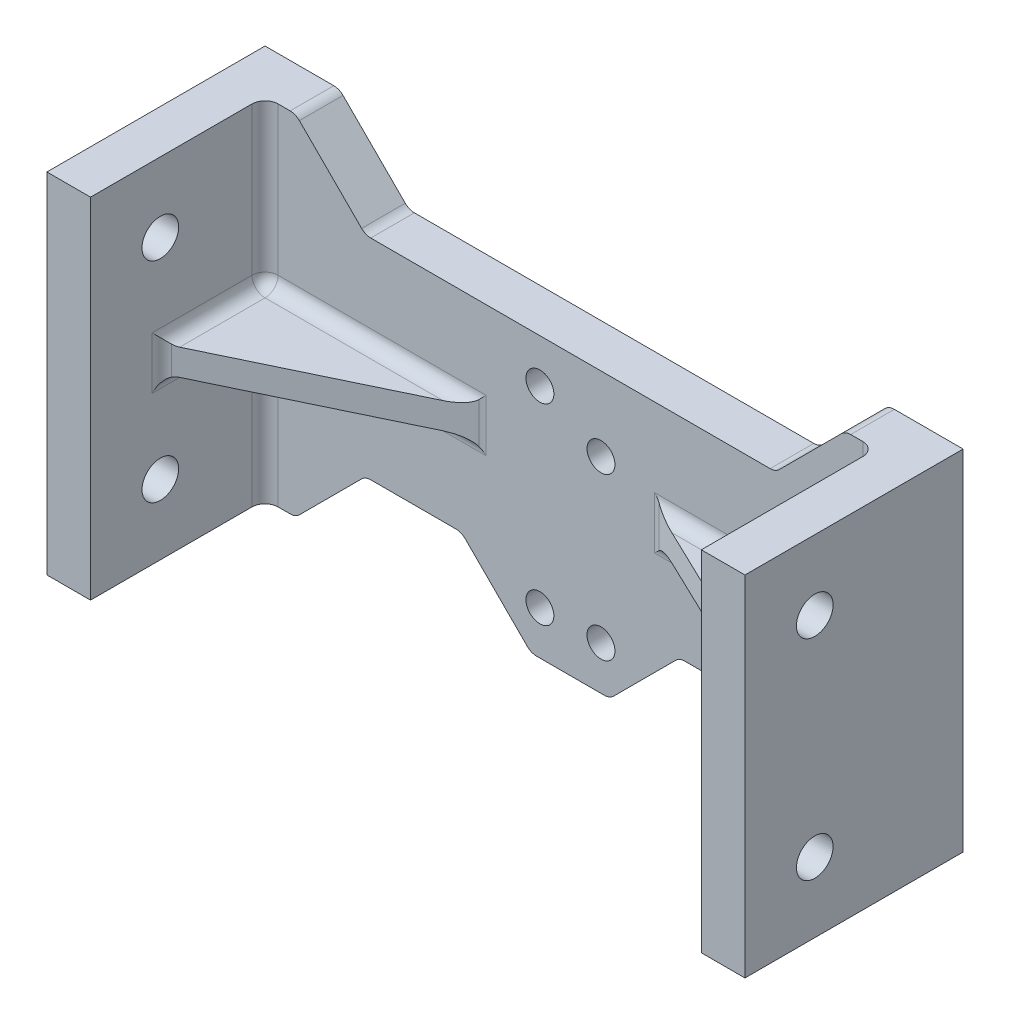
SolidWorks part; units mm, degrees
ref_plane "前视基准面" through (0, 0, 0) normal (0, 0, 1) x (1, 0, 0)
ref_plane "上视基准面" through (0, 0, 0) normal (0, 1, 0) x (1, 0, 0)
ref_plane "右视基准面" through (0, 0, 0) normal (1, 0, 0) x (0, 0, -1)
sketch "草图2" plane through (0, 4.7264, 0) normal (0, 1, 0) x (1, 0, 0)
  line L0 (21, 0) -> (-59, 0)
  line L2 (-59, 0) -> (-59, -25)
  line L3 (-59, -25) -> (-54, -25)
  line L5 (21, -25) -> (21, 0)
  line L6 (-54, -25) -> (-54, -5)
  line L7 (-54, -5) -> (16, -5)
  line L8 (16, -5) -> (16, -25)
  line L9 (16, -25) -> (21, -25)
  dimension "D1" = 5
  dimension "D2" = 5
  dimension "D3" = 5
  dimension "D4" = 20
  dimension "D5" = 70
extrude "凸台-拉伸1" add sketch "草图2" against normal blind 40
fillet "圆角1" radius 1.5 2 edges at (16, -15.2736, 5) (-54, -15.2736, 5)
sketch "草图3" plane through (0, 0, 5) normal (0, 0, 1) x (1, 0, 0)
  circle A1 centre (-22.5, -30.2736) radius 1.6
  circle A2 centre (-22.5, -8.2736) radius 1.6
  point P2 (-22.5, -33.2736)
  point P6 (-22.5, -11.2736)
  dimension "D1" = 3.2
  dimension "D2" = 3.2
extrude "切除-拉伸1" cut sketch "草图3" against normal blind 40
sketch "草图4" plane through (-59, 0, 0) normal (-1, 0, 0) x (0, 0, 1)
  line L0 (0, 4.7264) -> (25, 4.7264) construction
  line L1 (0, -35.2736) -> (25, -35.2736) construction
  line L2 (25, -35.2736) -> (25, 4.7264) construction
  circle A0 centre (17, -3.2736) radius 2.1
  circle A1 centre (17, -27.2736) radius 2.1
  dimension "D1" = 8
  dimension "D2" = 4.2
  dimension "D3" = 4.2
  dimension "D4" = 8
  dimension "D5" = 8
  dimension "D6" = 8
extrude "切除-拉伸2" cut sketch "草图4" against normal blind 80
sketch "草图5" plane through (0, 0, 5) normal (0, 0, 1) x (1, 0, 0)
  circle A1 centre (-15.5, -30.2736) radius 1.6
  circle A2 centre (-15.5, -11.7736) radius 1.6
  dimension "D1" = 3.2
  dimension "D2" = 3.2
extrude "切除-拉伸3" cut sketch "草图5" against normal blind 80
ref_plane "基准面1" through (0, -15.2736, 0) normal (0, -1, 0) x (-1, 0, 0)
sketch "草图6" plane through (0, -15.2736, 0) normal (0, -1, 0) x (-1, 0, 0)
  line L0 (-16, -17) -> (9, -5)
  line L1 (-16, -6.5) -> (-16, -25) construction
  line L2 (52.5, -5) -> (-14.5, -5) construction
  line L3 (9, -5) -> (-16, -5)
  line L4 (-16, -5) -> (-16, -17)
  dimension "D1" = 25
  dimension "D2" = 12
ref_plane "基准面3" through (-19, 0, 0) normal (-1, 0, 0) x (0, 0, 1)
sketch "草图7" plane through (0, 0, 5) normal (0, 0, 1) x (1, 0, 0)
  line L0 (-50.5, 4.7264) -> (-42.933, -2.8405)
  line L1 (-52.5, 4.7264) -> (14.5, 4.7264) construction
  line L2 (-41.8876, -3.2736) -> (3.8876, -3.2736)
  line L3 (4.933, -2.8405) -> (12.5, 4.7264)
  line L4 (12.5, 4.7264) -> (-50.5, 4.7264)
  line L5 (-59, -15.2736) -> (21, -15.2736) construction
  line L6 (-59, -35.2736) -> (-59, 4.7264) construction
  line L7 (21, -35.2736) -> (21, 4.7264) construction
  line L8 (12.5, -35.2736) -> (-14.5, -35.2736)
  line L9 (4.933, -27.7066) -> (12.5, -35.2736)
  line L10 (-41.8876, -27.2736) -> (-32.1213, -27.2736)
  line L11 (-50.5, -35.2736) -> (-42.933, -27.7066)
  line L12 (-31.0607, -27.7129) -> (-23.5, -35.2736)
  line L14 (-14.5, -35.2736) -> (-6.9393, -27.7129)
  line L15 (-5.8787, -27.2736) -> (3.8876, -27.2736)
  line L16 (-23.5, -35.2736) -> (-50.5, -35.2736)
  arc A0 (3.8876, -3.2736) -> (4.933, -2.8405) centre (3.8876, -1.7951) ccw
  arc A1 (-42.933, -2.8405) -> (-41.8876, -3.2736) centre (-41.8876, -1.7951) ccw
  arc A2 (-42.933, -27.7066) -> (-41.8876, -27.2736) centre (-41.8876, -28.7521) cw
  arc A3 (3.8876, -27.2736) -> (4.933, -27.7066) centre (3.8876, -28.7521) cw
  arc A4 (-6.9393, -27.7129) -> (-5.8787, -27.2736) centre (-5.8787, -28.7736) cw
  arc A5 (-31.0607, -27.7129) -> (-32.1213, -27.2736) centre (-32.1213, -28.7736) ccw
  point P32 (-6.5, -27.2736)
  dimension "D6" = 1.4785
  dimension "D11" = 1.5
  dimension "D1" = 2
  dimension "D2" = 2
  dimension "D3" = 8
  dimension "D4" = 45
  dimension "D5" = 45
  dimension "D7" = 27
  dimension "D8" = 27
  dimension "D9" = 45
  dimension "D10" = 45
extrude "切除-拉伸4" cut sketch "草图7" against normal blind 10
fillet "圆角4" radius 1.5 6 edges at (-50.5, -35.2736, 2.5) (-23.5, -35.2736, 2.5) (-14.5, -35.2736, 2.5) (12.5, -35.2736, 2.5) (12.5, 4.7264, 2.5) (-50.5, 4.7264, 2.5)
extrude "凸台-拉伸2" add sketch "草图6" along normal blind 1.5 and the other way blind 1.5
fillet "圆角5" radius 1.5 8 edges at (16, -13.7736, 11.75) (15.5607, -13.7736, 5.4393) (16, -16.7736, 11.75) (15.5607, -16.7736, 5.4393) (16, -15.2736, 17) (2.75, -13.7736, 5) (-9, -15.2736, 5) (2.75, -16.7736, 5)
mirror "镜向2" about plane through (-19, 0, 0) normal (-1, 0, 0) of "凸台-拉伸2"
fillet "圆角6" radius 1.5 8 edges at (-54, -13.7736, 11.75) (-53.5607, -13.7736, 5.4393) (-54, -16.7736, 11.75) (-53.5607, -16.7736, 5.4393) (-40.75, -13.7736, 5) (-29, -15.2736, 5) (-40.75, -16.7736, 5) (-54, -15.2736, 17)
